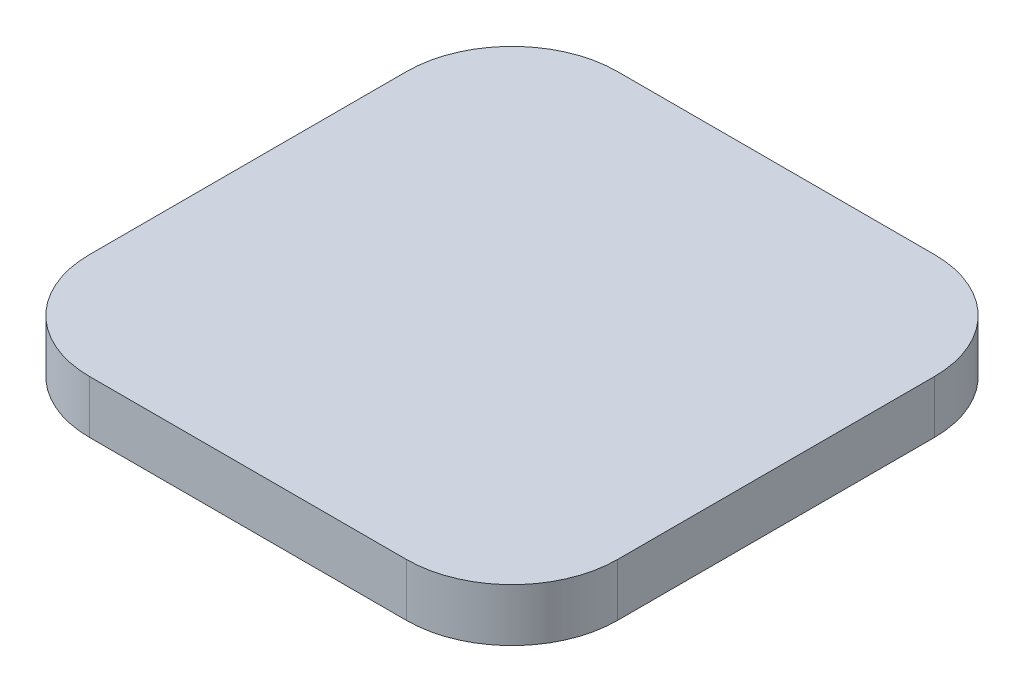
SolidWorks part; units mm, degrees
ref_plane "Front Plane" through (0, 0, 0) normal (0, 0, 1) x (1, 0, 0)
ref_plane "Top Plane" through (0, 0, 0) normal (0, 1, 0) x (1, 0, 0)
ref_plane "Right Plane" through (0, 0, 0) normal (1, 0, 0) x (0, 0, -1)
sketch "Sketch1" plane through (0, 0, 0) normal (0, 1, 0) x (1, 0, 0)
  line L1 (-25.4, -25.4) -> (25.4, -25.4)
  line L2 (-25.4, -25.4) -> (-25.4, 25.4)
  line L3 (-25.4, 25.4) -> (25.4, 25.4)
  line L4 (25.4, -25.4) -> (25.4, 25.4)
  line L5 (-25.4, -25.4) -> (25.4, 25.4) construction
  line L6 (-25.4, 25.4) -> (25.4, -25.4) construction
  point P0 (0, 0)
  dimension "D1" = 50.8
extrude "Boss-Extrude1" add sketch "Sketch1" along normal blind 5.08
fillet "Fillet1" radius 10.16 4 edges at (-25.4, 2.54, -25.4) (25.4, 2.54, -25.4) (25.4, 2.54, 25.4) (-25.4, 2.54, 25.4)
